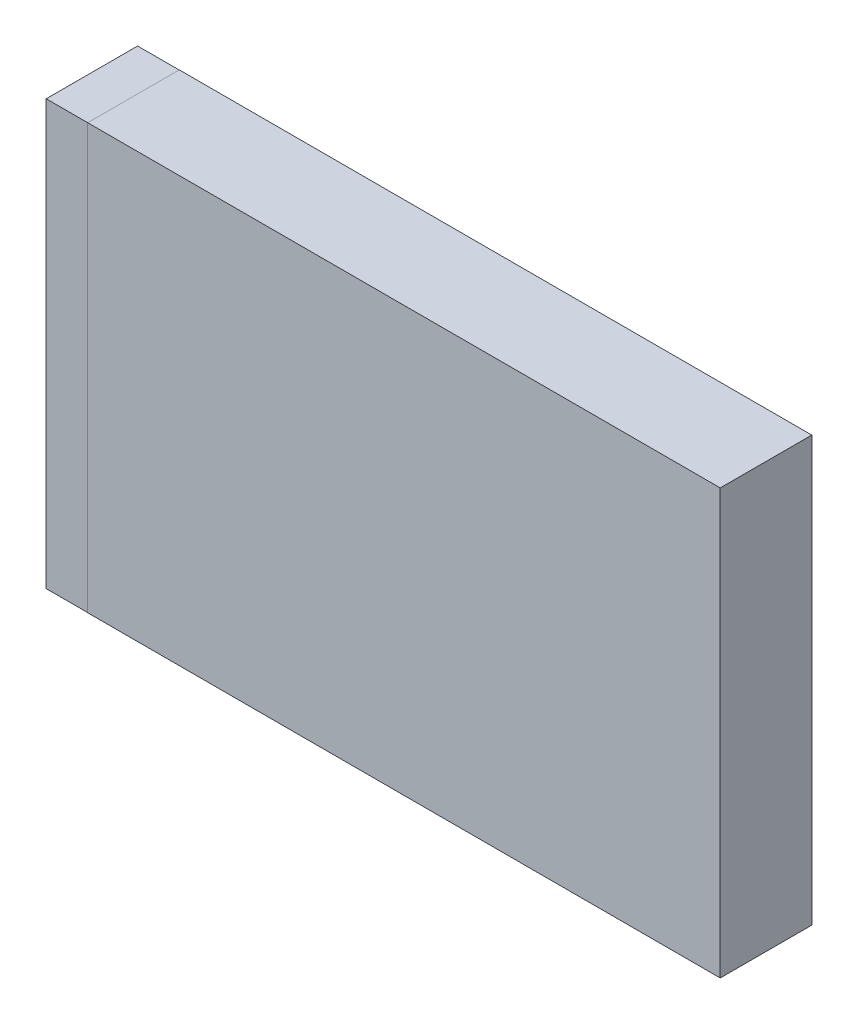
SolidWorks part; units mm, degrees
ref_plane "Front Plane" through (0, 0, 0) normal (0, 0, 1) x (1, 0, 0)
ref_plane "Top Plane" through (0, 0, 0) normal (0, 1, 0) x (1, 0, 0)
ref_plane "Right Plane" through (0, 0, 0) normal (1, 0, 0) x (0, 0, -1)
sketch "Sketch1" plane through (0, 0, 0) normal (0, 0, 1) x (1, 0, 0)
  line L1 (0, 0) -> (81, 0)
  line L2 (0, 0) -> (0, 51)
  line L3 (0, 51) -> (81, 51)
  line L4 (81, 0) -> (81, 51)
  dimension "D1" = 81
  dimension "D2" = 51
extrude "Boss-Extrude1" add sketch "Sketch1" along normal blind 11
sketch "Sketch2" plane through (0, 0, 11) normal (0, 0, 1) x (1, 0, 0)
  line L0 (0, 0) -> (81, 0) construction
  line L1 (0, 51) -> (5, 51)
  line L2 (0, 51) -> (0, 0)
  line L3 (0, 0) -> (5, 0)
  line L4 (5, 51) -> (5, 0)
  dimension "D1" = 5
extrude "Cut-Extrude1" cut sketch "Sketch2" against normal blind 0.01
sketch "Sketch3" plane through (0, 0, 0) normal (0, -1, 0) x (1, 0, 0)
  line L0 (0, 0) -> (81, 0) construction
  line L1 (0, 10.99) -> (5, 10.99)
  line L2 (0, 10.99) -> (0, 0)
  line L3 (0, 0) -> (5, 0)
  line L4 (5, 10.99) -> (5, 0)
  dimension "D1" = 5
extrude "Cut-Extrude2" cut sketch "Sketch3" against normal blind 0.01
sketch "Sketch4" plane through (0, 0, 0) normal (0, 0, -1) x (-1, 0, 0)
  line L0 (-81, 51) -> (0, 51) construction
  line L1 (0, 0) -> (-5, 0)
  line L2 (0, 0) -> (0, 51)
  line L3 (0, 51) -> (-5, 51)
  line L4 (-5, 0) -> (-5, 51)
  dimension "D1" = 5
extrude "Cut-Extrude3" cut sketch "Sketch4" against normal blind 0.01
sketch "Sketch5" plane through (0, 51, 0) normal (0, 1, 0) x (1, 0, 0)
  line L0 (81, -11) -> (5, -11) construction
  line L1 (0, 0) -> (5, 0)
  line L2 (0, 0) -> (0, -11)
  line L3 (0, -11) -> (5, -11)
  line L4 (5, 0) -> (5, -11)
  dimension "D1" = 5
extrude "Cut-Extrude4" cut sketch "Sketch5" against normal blind 0.01
